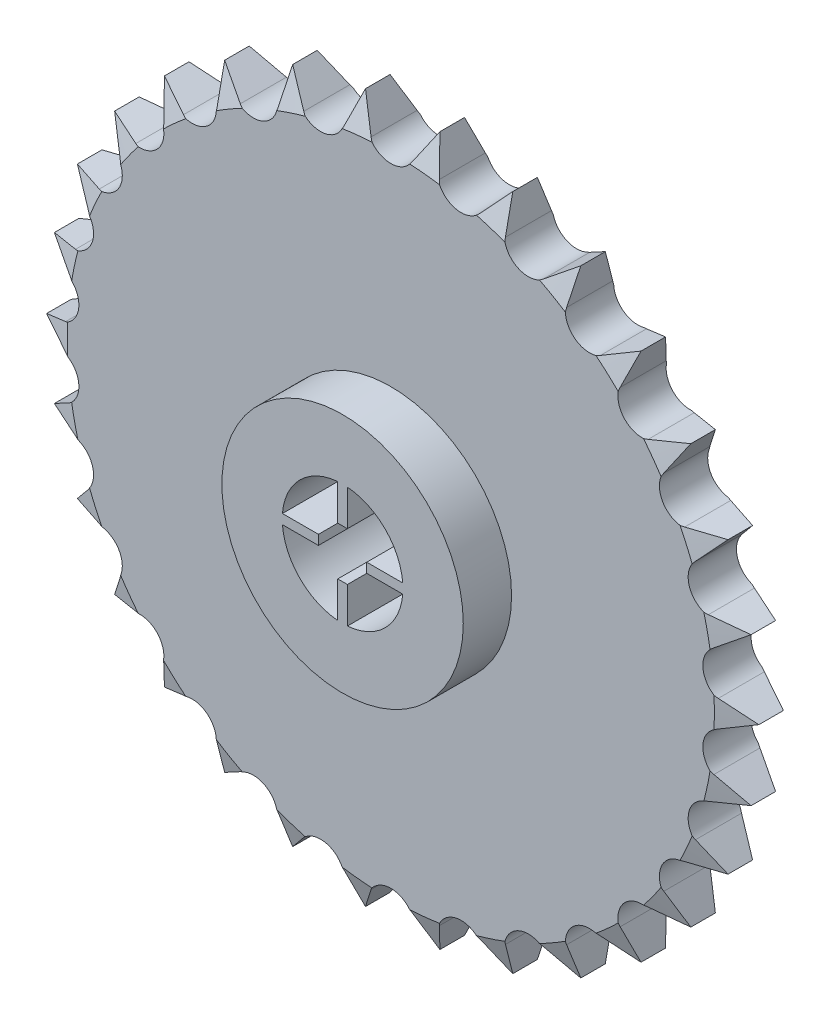
SolidWorks part; units mm, degrees
material "Sade Karbon Çeliği"
ref_plane "Ön Düzlem" through (0, 0, 0) normal (0, 0, 1) x (1, 0, 0)
ref_plane "Üst Düzlem" through (0, 0, 0) normal (0, 1, 0) x (1, 0, 0)
ref_plane "Sağ Düzlem" through (0, 0, 0) normal (1, 0, 0) x (0, 0, -1)
sketch "Çizim1" plane through (0, 0, 0) normal (0, 0, 1) x (1, 0, 0)
  circle A0 centre (0, 0) radius 25
  circle A1 centre (0, 0) radius 75
  circle A2 centre (0, 0) radius 70 construction
  dimension "D1" = 50
  dimension "D2" = 150
  dimension "D3" = 140
extrude "Yükseklik-Ekstrüzyon4" add sketch "Çizim1" against normal blind 10
sketch "Çizim3" plane through (0, 0, 0) normal (0, 0, 1) x (1, 0, 0)
  line L0 (-4.3301, 67.5) -> (-9.0426, 75.6623)
  line L1 (22.2188, 70) -> (-38.9742, 70) construction
  line L2 (0, 90.6243) -> (0, 67.8391) construction
  line L3 (4.3301, 67.5) -> (9.0426, 75.6623)
  circle A0 centre (0, 0) radius 70 construction
  arc A1 (-4.3301, 67.5) -> (4.3301, 67.5) centre (0, 70) ccw
  spline S0 degree 1 poles (-9.0426, 75.6623) (9.0426, 75.6623) knots 0 0 1 1
  dimension "D1" = 140
  dimension "D2" = 5
  dimension "60" = 60
extrude "Kes-Ekstrüzyon1" cut sketch "Çizim3" against normal blind 10
pattern_circular "Dairesel Kaplama1" count 30 every 12 about axis through (0, 0, 0) along (0, 0, 1) of "Kes-Ekstrüzyon1"
sketch "Çizim5" plane through (0, 0, 0) normal (0, 0, 1) x (1, 0, 0)
  arc A0 (-4.3301, 67.5) -> (4.3301, 67.5) centre (0, 70) ccw construction
  point P0 (0, 65)
sketch "Çizim7" plane through (0, 0, 0) normal (1, 0, 0) x (0, 0, -1)
  line L0 (0, 65) -> (10, 65) construction
  line L1 (0, 65) -> (0, 75) construction
  line L2 (0, 75) -> (10, 75) construction
  line L3 (10, 75) -> (10, 65) construction
  line L7 (0, 67) -> (2.9118, 75)
  line L8 (5, 65) -> (5, 71.9191) construction
  line L9 (0, 67) -> (0, 75)
  line L10 (0, 75) -> (2.9118, 75)
  line L11 (10, 67) -> (10, 75)
  line L12 (10, 67) -> (7.0882, 75)
  line L13 (10, 75) -> (7.0882, 75)
  dimension "D1" = 10
  dimension "D2" = 10
  dimension "D3" = 2
  dimension "D4" = 70
sketch "Çizim8" plane through (0, 0, 0) normal (1, 0, 0) x (0, 0, -1)
  line L0 (0, 0) -> (13.7721, 0) construction
revolve "Kes-Döndür2" cut sketch "Çizim7" angle 360 about L0
sketch "Çizim9" plane through (0, 0, 0) normal (0, 0, 1) x (1, 0, 0)
  circle A0 centre (0, 0) radius 25
  circle A1 centre (0, 0) radius 12.5
  dimension "D1" = 25
extrude "Yükseklik-Ekstrüzyon5" add sketch "Çizim9" along normal mid plane 30 from offset 5 offset against normal yes
sketch "Çizim10" plane through (0, 0, 10) normal (0, 0, 1) x (1, 0, 0)
  line L0 (12.5, 0) -> (5, 0) construction
  line L6 (-12.4599, 1) -> (-5, 1)
  line L9 (-12.4599, -1) -> (-5, -1)
  line L11 (1, 12.4599) -> (1, 5)
  line L12 (-1, 12.4599) -> (-1, 5)
  line L13 (-1, -5) -> (-1, -12.4599)
  line L14 (0, 5) -> (0, 12.5) construction
  line L15 (1, -5) -> (1, -12.4599)
  line L16 (5, 1) -> (12.4599, 1)
  line L17 (-5, 0) -> (-12.5, 0) construction
  line L18 (5, -1) -> (12.4599, -1)
  line L20 (-1, 5) -> (1, 5)
  line L21 (-5, 1) -> (-5, -1)
  line L22 (-1, -5) -> (1, -5)
  line L23 (5, 1) -> (5, -1)
  arc A5 (-1, -12.4599) -> (1, -12.4599) centre (0, 0) ccw
  arc A6 (-12.4599, 1) -> (-12.4599, -1) centre (0, 0) ccw
  arc A7 (1, 12.4599) -> (-1, 12.4599) centre (0, 0) ccw
  arc A8 (12.4599, -1) -> (12.4599, 1) centre (0, 0) ccw
  dimension "D1" = 1
extrude "Yükseklik-Ekstrüzyon6" add sketch "Çizim10" against normal blind 30
ref_plane "Düzlem1" through (0, 0, -5) normal (0, 0, 1) x (1, 0, 0)
sketch "Çizim15" plane through (0, 0, -5) normal (0, 0, 1) x (1, 0, 0)
  line L0 (-242.5017, -9.436) -> (-22.7815, 66.1891)
  line L1 (-232.3704, -70.0009) -> (0.0003, -70)
  arc A0 (0.0003, -70) -> (-22.7815, 66.1891) centre (0, 0) ccw
  arc A1 (-242.5017, -9.436) -> (-232.3704, -70.0009) centre (-232.3705, -38.8711) ccw
  dimension "D1" = 70
